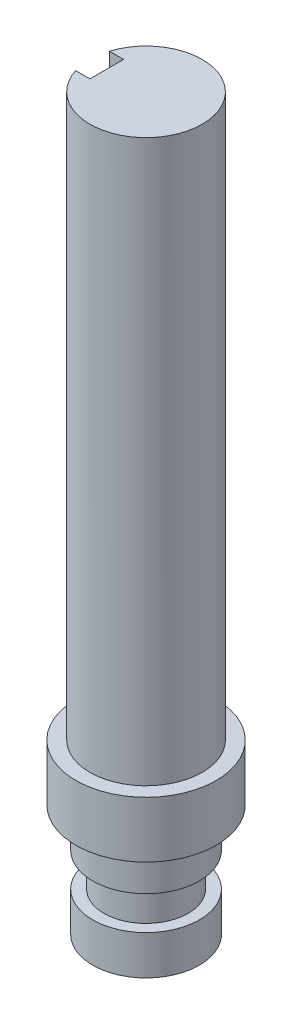
SolidWorks part; units mm, degrees
ref_plane "Front Plane" through (0, 0, 0) normal (0, 0, 1) x (1, 0, 0)
ref_plane "Top Plane" through (0, 0, 0) normal (0, 1, 0) x (1, 0, 0)
ref_plane "Right Plane" through (0, 0, 0) normal (1, 0, 0) x (0, 0, -1)
sketch "Sketch1" plane through (0, 0, 0) normal (0, 1, 0) x (1, 0, 0)
  circle A0 centre (0, 0) radius 10
  dimension "D1" = 20
extrude "Boss-Extrude1" add sketch "Sketch1" along normal mid plane 100
sketch "Sketch2" plane through (0, -50, 0) normal (0, -1, 0) x (1, 0, 0)
  circle A0 centre (0, 0) radius 12.5
  dimension "D1" = 25
extrude "Boss-Extrude2" add sketch "Sketch2" along normal blind 10
sketch "Sketch3" plane through (0, -60, 0) normal (0, -1, 0) x (1, 0, 0)
  circle A0 centre (0, 0) radius 9.5
  dimension "D1" = 19
extrude "Boss-Extrude3" add sketch "Sketch3" along normal blind 7
sketch "Sketch4" plane through (0, -67, 0) normal (0, -1, 0) x (1, 0, 0)
  circle A0 centre (0, 0) radius 7.5
  dimension "D1" = 15
extrude "Boss-Extrude4" add sketch "Sketch4" along normal blind 6
sketch "Sketch5" plane through (0, -73, 0) normal (0, -1, 0) x (1, 0, 0)
  circle A0 centre (0, 0) radius 9.5
  dimension "D1" = 19
extrude "Boss-Extrude5" add sketch "Sketch5" along normal blind 7
sketch "Sketch6" plane through (0, 50, 0) normal (0, 1, 0) x (1, 0, 0)
  line L1 (-7, -3) -> (-13, -3)
  line L2 (-7, -3) -> (-7, 3)
  line L3 (-7, 3) -> (-13, 3)
  line L4 (-13, -3) -> (-13, 3)
  line L5 (-7, -3) -> (-13, 3) construction
  line L6 (-7, 3) -> (-13, -3) construction
  circle A0 centre (0, 0) radius 10 construction
  circle A1 centre (0, 0) radius 10 construction
  point P0 (-10, 0)
  dimension "D1" = 7
  dimension "D2" = 6
extrude "Cut-Extrude1" cut sketch "Sketch6" against normal blind 20
